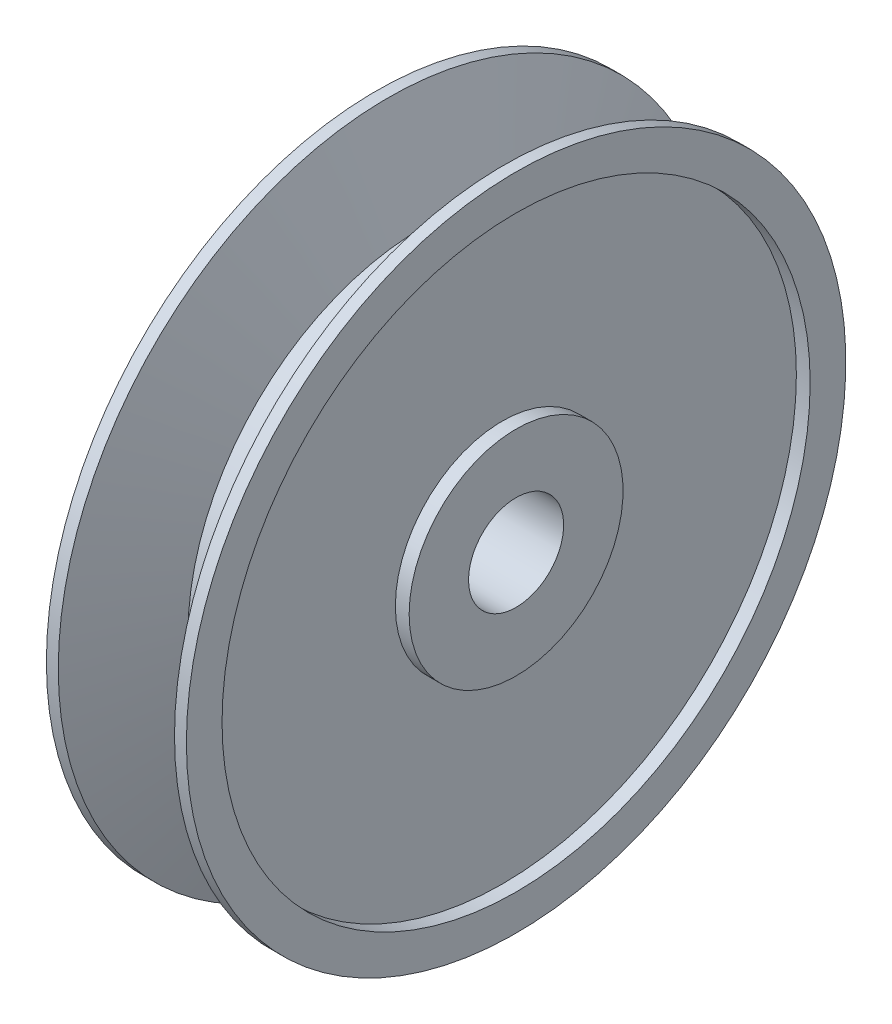
SolidWorks part; units mm, degrees
ref_plane "Front Plane" through (0, 0, 0) normal (0, 0, 1) x (1, 0, 0)
ref_plane "Top Plane" through (0, 0, 0) normal (0, 1, 0) x (1, 0, 0)
ref_plane "Right Plane" through (0, 0, 0) normal (1, 0, 0) x (0, 0, -1)
sketch "Sketch1" plane through (0, 0, 0) normal (0, 0, 1) x (1, 0, 0)
  line L0 (0, 0) -> (27.1229, 0) construction
  line L2 (0, 4) -> (5.89, 4)
  line L3 (5.89, 4) -> (5.89, 9)
  line L4 (5.89, 9) -> (4.7309, 9)
  line L5 (4.7309, 9) -> (4.7309, 24.74)
  line L6 (4.7309, 24.74) -> (5.89, 24.74)
  line L7 (5.89, 24.74) -> (5.89, 27.74)
  line L8 (5.89, 27.74) -> (0, 27.74)
  line L9 (0, 27.74) -> (0, 4)
  point P4 (0, 0)
  point P11 (27.1229, 0)
  dimension "D1" = 4
  dimension "D2" = 5.89
  dimension "D3" = 23.74
  dimension "D4" = 3
  dimension "D5" = 5
  dimension "D6" = 5.89
revolve "Revolve1" add sketch "Sketch1" angle 360 about L0
sketch "Sketch2" plane through (0, 0, 0) normal (0, 0, 1) x (1, 0, 0)
  line L0 (0, 0) -> (10.1425, 0) construction
  line L2 (0, 19.74) -> (1.9778, 19.74)
  line L3 (1.9778, 19.74) -> (4.8896, 27.74)
  line L4 (5.89, 27.74) -> (0, 27.74) construction
  line L5 (4.8896, 27.74) -> (0, 27.74)
  line L6 (0, 27.74) -> (0, 19.74)
  dimension "D1" = 110
  dimension "D2" = 8
revolve "Cut-Revolve1" cut sketch "Sketch2" angle 360 about L0
mirror "Mirror1" about plane through (0, 27.74, 0) normal (1, 0, 0) of "Revolve1", "Cut-Revolve1"
